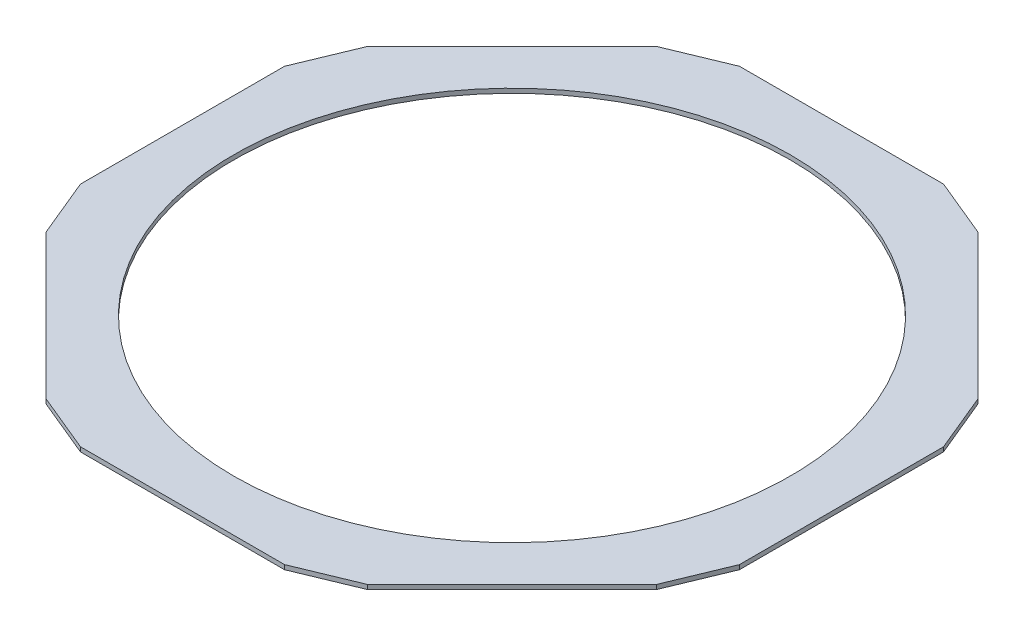
SolidWorks part; units mm, degrees
material "PBT General Purpose"
ref_plane "Front Plane" through (0, 0, 0) normal (0, 0, 1) x (1, 0, 0)
ref_plane "Top Plane" through (0, 0, 0) normal (0, 1, 0) x (1, 0, 0)
ref_plane "Right Plane" through (0, 0, 0) normal (1, 0, 0) x (0, 0, -1)
sketch "Sketch1" plane through (0, 0, 0) normal (0, 1, 0) x (1, 0, 0)
  line L0 (0, 0) -> (11, 0)
  line L1 (11, 0) -> (14.1689, 1.3126)
  line L2 (14.1689, 1.3126) -> (21.9471, 9.0908)
  line L3 (21.9471, 9.0908) -> (23.2597, 12.2597)
  line L4 (23.2597, 12.2597) -> (23.2597, 23.2597)
  line L5 (23.2597, 23.2597) -> (21.9471, 26.4286)
  line L6 (21.9471, 26.4286) -> (14.1689, 34.2068)
  line L7 (14.1689, 34.2068) -> (11, 35.5194)
  line L8 (11, 35.5194) -> (0, 35.5194)
  line L9 (0, 35.5194) -> (-3.1689, 34.2068)
  line L10 (-3.1689, 34.2068) -> (-10.9471, 26.4286)
  line L11 (-10.9471, 26.4286) -> (-12.2597, 23.2597)
  line L12 (-12.2597, 23.2597) -> (-12.2597, 12.2597)
  line L13 (-12.2597, 12.2597) -> (-10.9471, 9.0908)
  line L14 (-3.1689, 1.3126) -> (0, 0)
  line L15 (-3.1689, 1.3126) -> (-10.9471, 9.0908)
  line L16 (-10.9471, 9.0908) -> (21.9471, 26.4286) construction
  circle A0 centre (5.5, 17.7597) radius 15
  dimension "D25" = 30
  dimension "D1" = 11
  dimension "D2" = 11
  dimension "D3" = 11
  dimension "D4" = 11
  dimension "D5" = 11
  dimension "D6" = 11
  dimension "D7" = 11
  dimension "D8" = 11
  dimension "D9" = 3.43
  dimension "D10" = 3.43
  dimension "D11" = 3.43
  dimension "D12" = 3.43
  dimension "D13" = 3.43
  dimension "D14" = 3.43
  dimension "D15" = 3.43
  dimension "D16" = 3.43
  dimension "D17" = 135
  dimension "D18" = 135
  dimension "D19" = 157.5
  dimension "D20" = 157.5
  dimension "D21" = 157.5
  dimension "D22" = 157.5
  dimension "D23" = 157.5
  dimension "D24" = 157.5
extrude "Boss-Extrude1" add sketch "Sketch1" along normal blind 0.24
